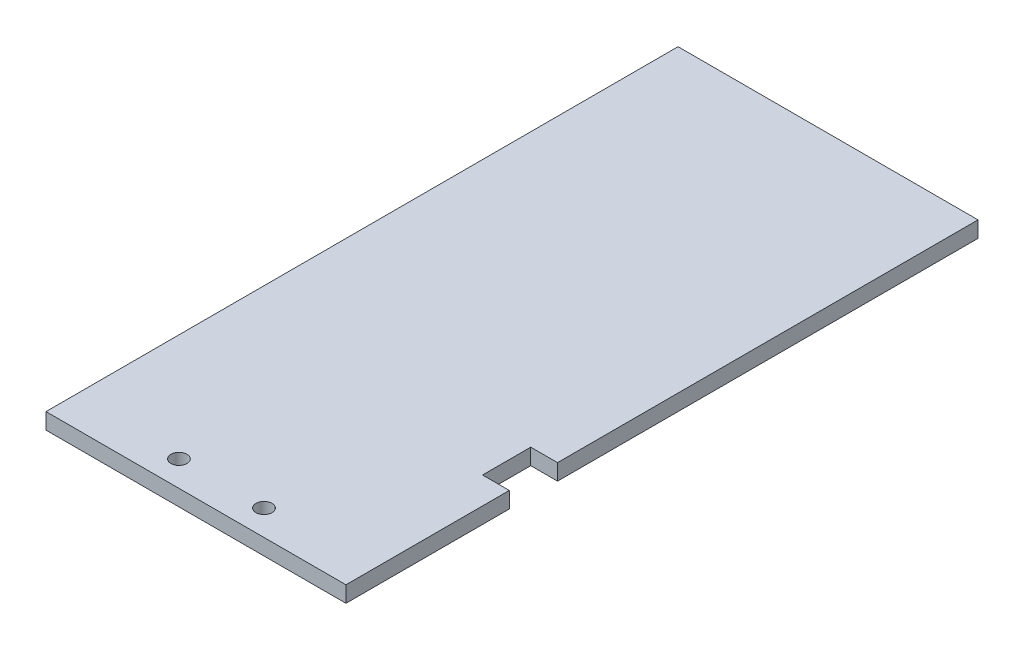
SolidWorks part; units mm, degrees
material "Acrilico TEC"
ref_plane "Front Plane" through (0, 0, 0) normal (0, 0, 1) x (1, 0, 0)
ref_plane "Top Plane" through (0, 0, 0) normal (0, 1, 0) x (1, 0, 0)
ref_plane "Right Plane" through (0, 0, 0) normal (1, 0, 0) x (0, 0, -1)
sketch "Sketch1" plane through (0, 0, 0) normal (0, 1, 0) x (1, 0, 0)
  line L1 (0, 0) -> (56, 0)
  line L2 (0, 0) -> (0, 98)
  line L3 (0, 98) -> (56, 98)
  line L4 (56, 0) -> (56, 98)
  dimension "D1" = 56
  dimension "D2" = 98
extrude "Boss-Extrude1" add sketch "Sketch1" along normal blind 3
sketch "Sketch4" plane through (0, 0, 0) normal (0, 0, 1) x (1, 0, 0)
  line L1 (0, 0) -> (56, 0)
  line L2 (0, 0) -> (0, 3)
  line L3 (0, 3) -> (56, 3)
  line L4 (56, 0) -> (56, 3)
extrude "Boss-Extrude3" add sketch "Sketch4" along normal blind 20
sketch "Sketch9" plane through (0, 3, 0) normal (0, 1, 0) x (1, 0, 0)
  line L0 (56, -20) -> (56, 98) construction
  line L1 (51, 10.5) -> (56, 10.5)
  line L2 (51, 10.5) -> (51, 19.5)
  line L3 (51, 19.5) -> (56, 19.5)
  line L4 (56, 10.5) -> (56, 19.5)
  point P6 (56, 39)
  point P7 (56, 15)
  dimension "D1" = 9
  dimension "D2" = 5
  dimension "D3" = 10.5
extrude "Cut-Extrude1" cut sketch "Sketch9" against normal blind 10
sketch "Croquis1" plane through (0, 3, 0) normal (0, 1, 0) x (1, 0, 0)
  line L0 (28, -20) -> (28, -4.9957) construction
  line L1 (56, -20) -> (0, -20) construction
  line L2 (28, -4.9957) -> (28, 98) construction
  line L3 (56, 98) -> (0, 98) construction
  circle A0 centre (20.06, -15.24) radius 1.5
  circle A1 centre (35.94, -15.24) radius 1.5
  dimension "D2" = 3
  dimension "D1" = 7.94
  dimension "D3" = 4.76
extrude "Cortar-Extruir1" cut sketch "Croquis1" against normal blind 10
